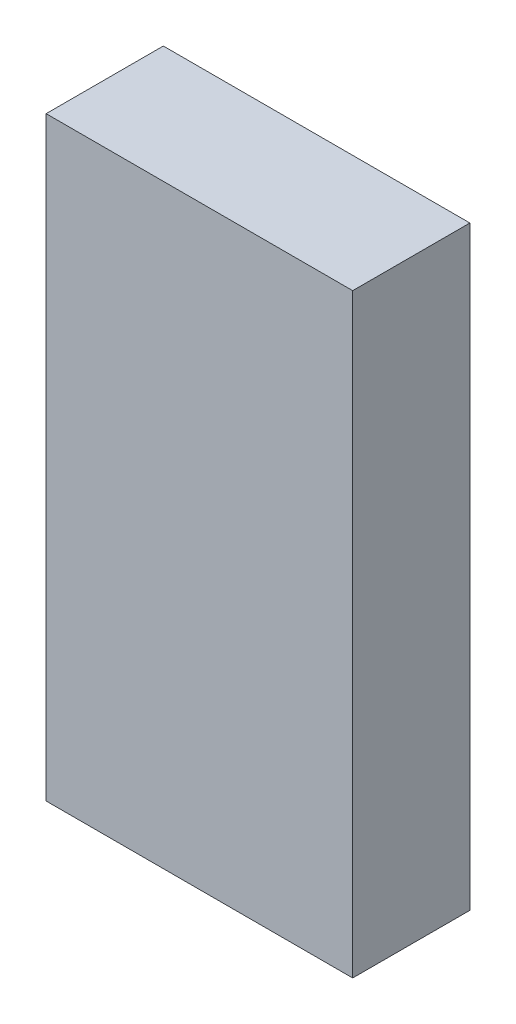
SolidWorks part; units mm, degrees
ref_plane "Front Plane" through (0, 0, 0) normal (0, 0, 1) x (1, 0, 0)
ref_plane "Top Plane" through (0, 0, 0) normal (0, 1, 0) x (1, 0, 0)
ref_plane "Right Plane" through (0, 0, 0) normal (1, 0, 0) x (0, 0, -1)
sketch "Sketch1" plane through (0, 0, 0) normal (0, 0, 1) x (1, 0, 0)
  line L0 (-1.3462, 2.54) -> (1.27, 2.54)
  line L1 (1.27, 2.54) -> (1.27, -2.54)
  line L2 (1.27, -2.54) -> (-1.3462, -2.54)
  line L3 (-1.3462, -2.54) -> (-1.3462, 2.54)
extrude "Component_Outline" add sketch "Sketch1" along normal blind 1 separate body
sketch3d "3DSketch1"
  line L0 (0, 0, 0) -> (1, 0, 0)
  line L1 (0, 0, 0) -> (0, 1, 0)
  line L2 (0, 0, 0) -> (0, 0, 1)
  point P0 (0, 0, 0)
